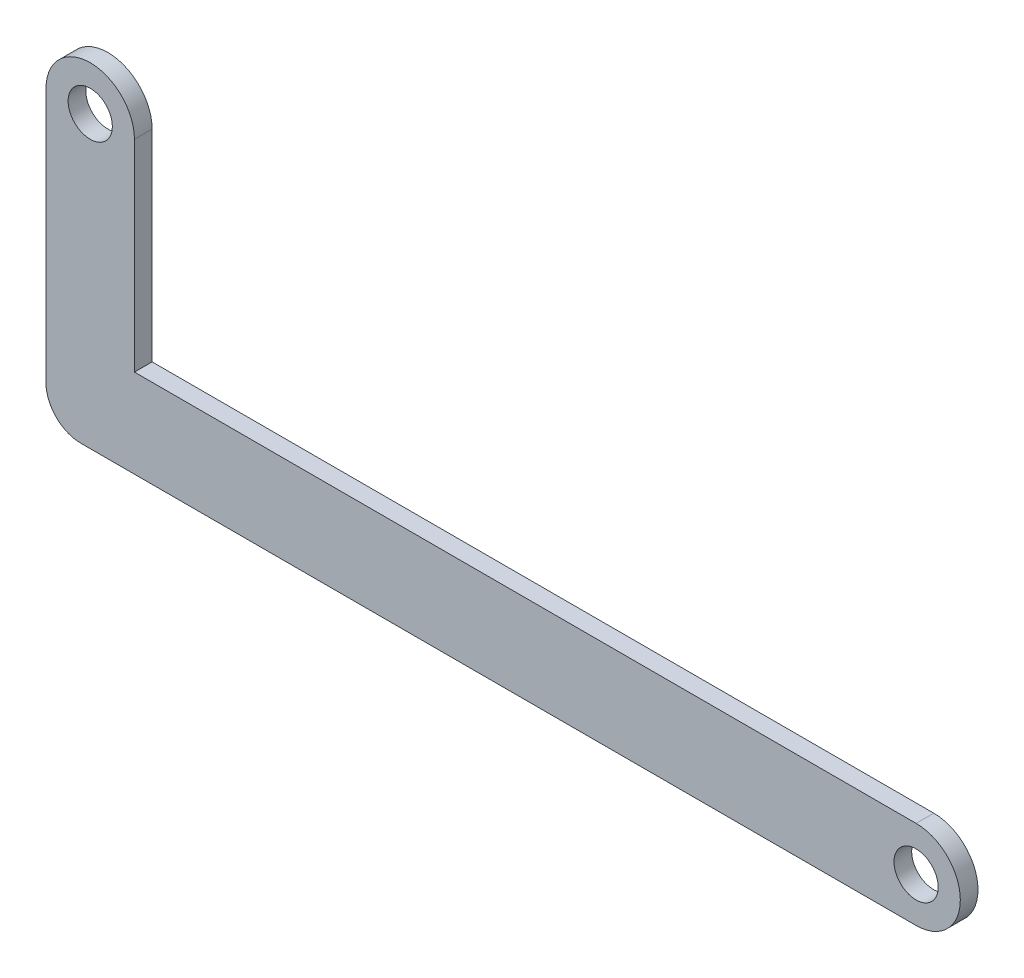
SolidWorks part; units mm, degrees
ref_plane "Front Plane" through (0, 0, 0) normal (0, 0, 1) x (1, 0, 0)
ref_plane "Top Plane" through (0, 0, 0) normal (0, 1, 0) x (1, 0, 0)
ref_plane "Right Plane" through (0, 0, 0) normal (1, 0, 0) x (0, 0, -1)
sketch "Sketch2" plane through (0, 0, 0) normal (0, 0, -1) x (1, 0, 0)
  line L13 (-237.2, -70.6) -> (-224.5, -70.6) construction
  line L14 (-237.2, -70.6) -> (-249.9, -70.6) construction
  line L15 (-237.2, -70.6) -> (-237.2, -83.3) construction
  line L16 (0, 0) -> (0, 12.7) construction
  line L17 (0, 0) -> (0, -12.7) construction
  line L18 (0, 0) -> (12.7, 0) construction
  line L19 (-237.2, 0) -> (-237.2, -70.6) construction
  line L20 (0, 0) -> (-237.2, 0) construction
  line L21 (-249.9, -70.6) -> (-249.9, 2.7)
  line L22 (-224.5, -12.7) -> (-224.5, -70.6)
  line L23 (0, -12.7) -> (-224.5, -12.7)
  line L24 (0, 12.7) -> (-239.9, 12.7)
  circle A0 centre (0, 0) radius 6.35
  arc A2 (0, 12.7) -> (0, -12.7) centre (0, 0) cw
  arc A5 (-239.9, 12.7) -> (-249.9, 2.7) centre (-239.9, 2.7) ccw
  arc A6 (-249.9, -70.6) -> (-224.5, -70.6) centre (-237.2, -70.6) ccw
  circle A7 centre (-237.2, -70.6) radius 6.35
  point P0 (-237.2, -84.8546)
  point P3 (0, 0)
  dimension "D1" = 12.7
  dimension "D4" = 237.2
  dimension "D5" = 12.7
  dimension "D9" = 10
  dimension "D2" = 70.6
  dimension "D3" = 25.4
  dimension "D6" = 12.7
  dimension "D7" = 12.7
  dimension "D8" = 25.4
extrude "Boss-Extrude1" add sketch "Sketch2" along normal blind 5.08
